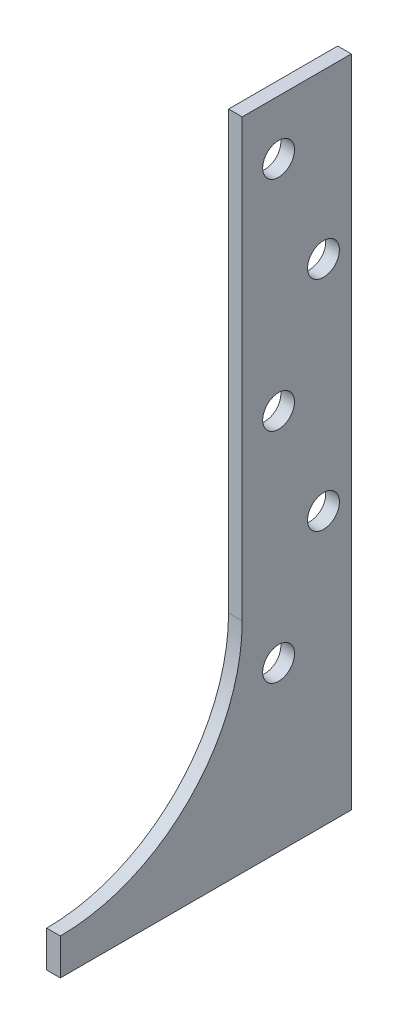
SolidWorks part; units mm, degrees
material "Pine"
ref_plane "Front Plane" through (0, 0, 0) normal (0, 0, 1) x (1, 0, 0)
ref_plane "Top Plane" through (0, 0, 0) normal (0, 1, 0) x (1, 0, 0)
ref_plane "Right Plane" through (0, 0, 0) normal (1, 0, 0) x (0, 0, -1)
sketch "Sketch1" plane through (0, 0, 0) normal (1, 0, 0) x (0, 0, -1)
  line L0 (-152.4, 914.4) -> (-152.4, 304.8)
  line L1 (0, 0) -> (-406.4, 0)
  line L2 (0, 914.4) -> (0, 0)
  line L3 (-101.6, 511.175) -> (-101.6, 533.4) construction
  line L4 (-406.4, 0) -> (-406.4, 50.8)
  line L5 (-101.6, 533.4) -> (-101.6, 685.8) construction
  line L6 (-101.6, 685.8) -> (-101.6, 838.2) construction
  line L7 (-101.6, 838.2) -> (-101.6, 914.4) construction
  line L8 (-101.6, 533.4) -> (-101.6, 381) construction
  line L9 (-101.6, 381) -> (-101.6, 228.6) construction
  line L10 (-101.6, 228.6) -> (-101.6, 0) construction
  line L11 (-38.8738, 0) -> (-38.8738, 381) construction
  line L12 (-38.8738, 381) -> (-38.8738, 685.8) construction
  line L13 (-38.8738, 685.8) -> (-38.8738, 914.4) construction
  line L17 (-152.4, 914.4) -> (0, 914.4)
  arc A0 (-152.4, 304.8) -> (-406.4, 50.8) centre (-406.4, 304.8) cw
  circle A1 centre (-101.6, 838.2) radius 22.225
  circle A2 centre (-38.8738, 685.8) radius 22.225
  circle A3 centre (-101.6, 533.4) radius 22.225
  circle A4 centre (-38.8738, 381) radius 22.225
  circle A5 centre (-101.6, 228.6) radius 22.225
  dimension "D4" = 254
  dimension "D6" = 44.45
  dimension "D7" = 44.45
  dimension "D8" = 44.45
  dimension "D15" = 44.45
  dimension "D16" = 44.45
  dimension "D1" = 406.4
  dimension "D2" = 914.4
  dimension "D3" = 152.4
  dimension "D5" = 50.8
  dimension "D9" = 101.6
  dimension "D10" = 76.2
  dimension "D11" = 152.4
  dimension "D12" = 152.4
  dimension "D13" = 152.4
  dimension "D14" = 152.4
  dimension "D17" = 228.6
  dimension "D18" = 304.8
extrude "Boss-Extrude1" add sketch "Sketch1" along normal blind 19.05
